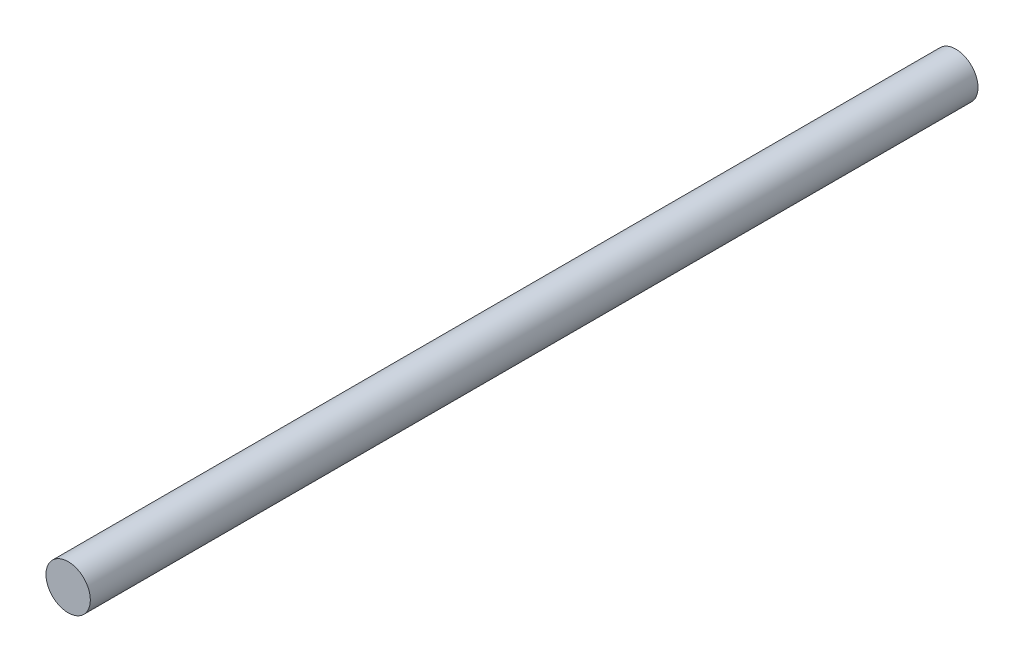
SolidWorks part; units mm, degrees
material "Литая легированная сталь"
ref_plane "Спереди" through (0, 0, 0) normal (0, 0, 1) x (1, 0, 0)
ref_plane "Сверху" through (0, 0, 0) normal (0, 1, 0) x (1, 0, 0)
ref_plane "Справа" through (0, 0, 0) normal (1, 0, 0) x (0, 0, -1)
sketch "Эскиз1" plane through (0, 0, 0) normal (0, 1, 0) x (1, 0, 0)
  line L0 (4, 0) -> (0, 0)
  line L1 (0, 0) -> (0, -160)
  line L2 (0, -160) -> (4, -160)
  line L3 (4, -160) -> (4, 0)
  line L4 (0, 0) -> (0, -160) construction
  dimension "D1" = 160
revolve "Повернуть1" add sketch "Эскиз1" angle 360 about L4
